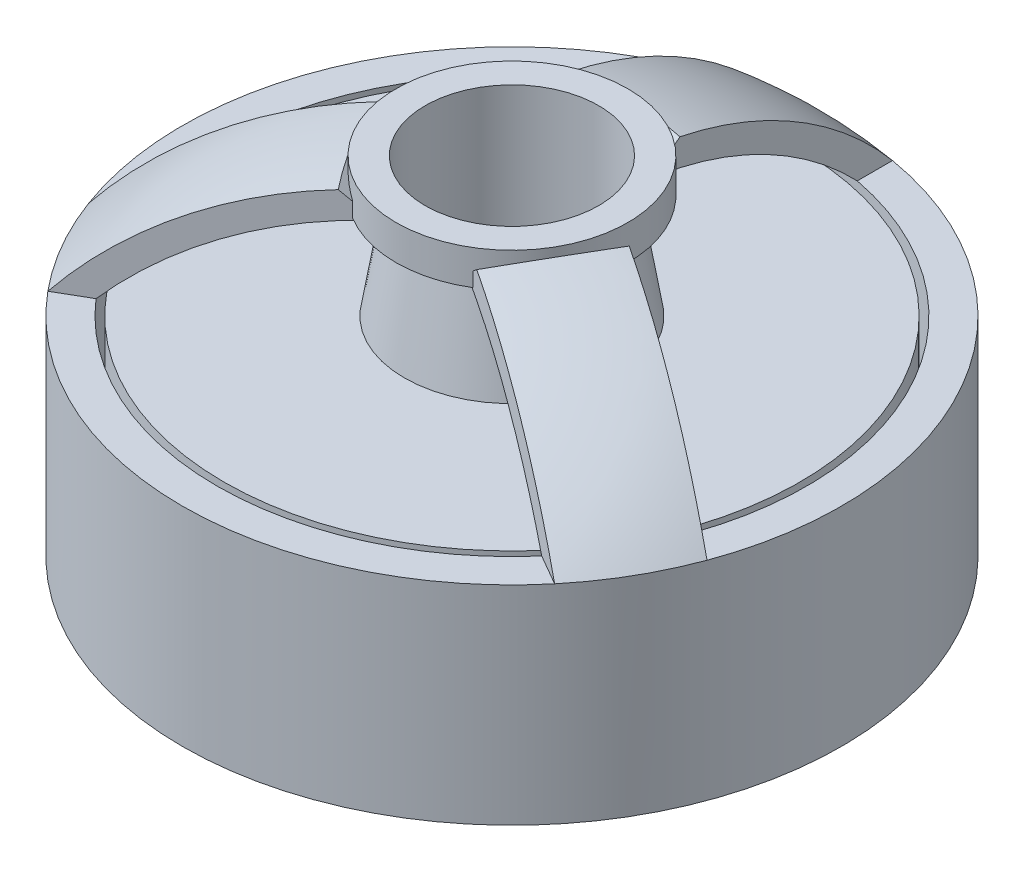
SolidWorks part; units mm, degrees
ref_plane "Front Plane" through (0, 0, 0) normal (0, 0, 1) x (1, 0, 0)
ref_plane "Top Plane" through (0, 0, 0) normal (0, 1, 0) x (1, 0, 0)
ref_plane "Right Plane" through (0, 0, 0) normal (1, 0, 0) x (0, 0, -1)
sketch "Sketch1" plane through (0, 0, 0) normal (0, 1, 0) x (1, 0, 0)
  circle A0 centre (0, 0) radius 47.5
  dimension "D1" = 95
extrude "Boss-Extrude1" add sketch "Sketch1" along normal blind 30
sketch "Sketch2" plane through (0, 30, 0) normal (0, 1, 0) x (1, 0, 0)
  circle A0 centre (0, 0) radius 12.5
  dimension "D1" = 25
extrude "Cut-Extrude1" cut sketch "Sketch2" against normal blind 30
sketch "Sketch3" plane through (0, 30, 0) normal (0, 1, 0) x (1, 0, 0)
  circle A2 centre (0, 0) radius 41.5
  circle A4 centre (0, 0) radius 47.5 construction
  circle A6 centre (0, 0) radius 42.5
  dimension "D2" = 5
  dimension "D1" = 1
extrude "Cut-Extrude3" cut sketch "Sketch3" against normal through all contours A2
sketch "Sketch5" plane through (0, 30, 0) normal (0, 1, 0) x (1, 0, 0)
  circle A3 centre (0, 0) radius 42
  circle A5 centre (0, 0) radius 15.5
  circle A6 centre (0, 0) radius 15.5
  dimension "D1" = 3
ref_plane "Plane1" through (0, 45, 0) normal (0, -1, 0) x (-1, 0, 0)
sketch "Sketch6" plane through (0, 45, 0) normal (0, -1, 0) x (-1, 0, 0)
  circle A0 centre (0, 0) radius 13
  dimension "D1" = 26
loft "Loft1" add profiles "Sketch6" section "Sketch6" section "Sketch5"
sketch "Sketch9" plane through (0, 45, 0) normal (0, 1, 0) x (1, 0, 0)
  circle A2 centre (0, 0) radius 12
  circle A3 centre (0, 0) radius 12
  dimension "D1" = 1
extrude "Cut-Extrude4" cut sketch "Sketch9" against normal through all
sketch "Sketch10" plane through (0, 30, 0) normal (0, 1, 0) x (1, 0, 0)
  line L2 (8.0398, 41.7326) -> (8.0398, 46.8147)
  line L4 (-8.0398, 41.7326) -> (-8.0398, 46.8147)
  circle A0 centre (0, 0) radius 42.5 construction
  circle A1 centre (0, 0) radius 47.5 construction
  arc A2 (8.0398, 41.7326) -> (-8.0398, 41.7326) centre (0, 0) ccw
  arc A3 (8.0398, 46.8147) -> (-8.0398, 46.8147) centre (0, 0) ccw
sketch "Sketch13" plane through (0, 0, 0) normal (1, 0, 0) x (0, 0, -1)
  arc A0 (12, 45) -> (41.5, 30) centre (5.1244, -5.0304) cw
sweep "Sweep1" add profiles "Sketch10" path "Sketch13"
pattern_circular "CirPattern1" count 3 over 360 about axis through (0, 30, 0) along (0, 1, 0) of "Sweep1"
ref_plane "Plane2" through (0, 50, 0) normal (0, -1, 0) x (-1, 0, 0)
sketch "Sketch18" plane through (0, 50, 0) normal (0, -1, 0) x (-1, 0, 0)
  circle A0 centre (0, 0) radius 16.7116
  ellipse E0 centre (-17.8304, 10.2944) end of major axis (5.9196, 51.4306) minor radius 37.3004 (9.9867, -15.0494) -> (18.0265, -1.1241) ccw construction
extrude "Boss-Extrude3" add sketch "Sketch18" along a picked direction on the side of the normal blind 5 contours A0
sketch "Sketch19" plane through (0, 50, 0) normal (0, 1, 0) x (1, 0, 0)
  circle A0 centre (0, 0) radius 12.5
  dimension "D1" = 25
extrude "Cut-Extrude5" cut sketch "Sketch19" against normal through all contours A0
